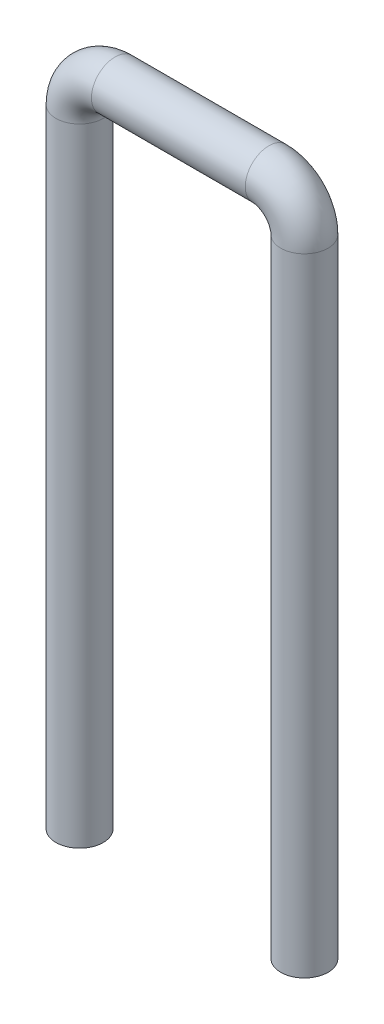
SolidWorks part; units mm, degrees
material "Acier non allié"
ref_plane "Plan de face" through (0, 0, 0) normal (0, 0, 1) x (1, 0, 0)
ref_plane "Plan de dessus" through (0, 0, 0) normal (0, 1, 0) x (1, 0, 0)
ref_plane "Plan de droite" through (0, 0, 0) normal (1, 0, 0) x (0, 0, -1)
sketch "Esquisse1" plane through (0, 0, 0) normal (0, 0, 1) x (1, 0, 0)
  line L0 (0, 0) -> (0, 53)
  line L1 (3, 56) -> (16, 56)
  line L2 (19, 53) -> (19, 0)
  line L3 (0, 0) -> (19, 0) construction
  arc A0 (19, 53) -> (16, 56) centre (16, 53) ccw
  arc A1 (3, 56) -> (0, 53) centre (3, 53) ccw
  point P7 (19, 56)
  point P10 (0, 56)
  dimension "D3" = 3
  dimension "D1" = 56
  dimension "D2" = 19
sketch "Esquisse2" plane through (0, 0, 0) normal (0, 1, 0) x (1, 0, 0)
  circle A0 centre (0, 0) radius 2
  dimension "D1" = 4
sweep "Balayage1" add profiles "Esquisse2" path "Esquisse1"
